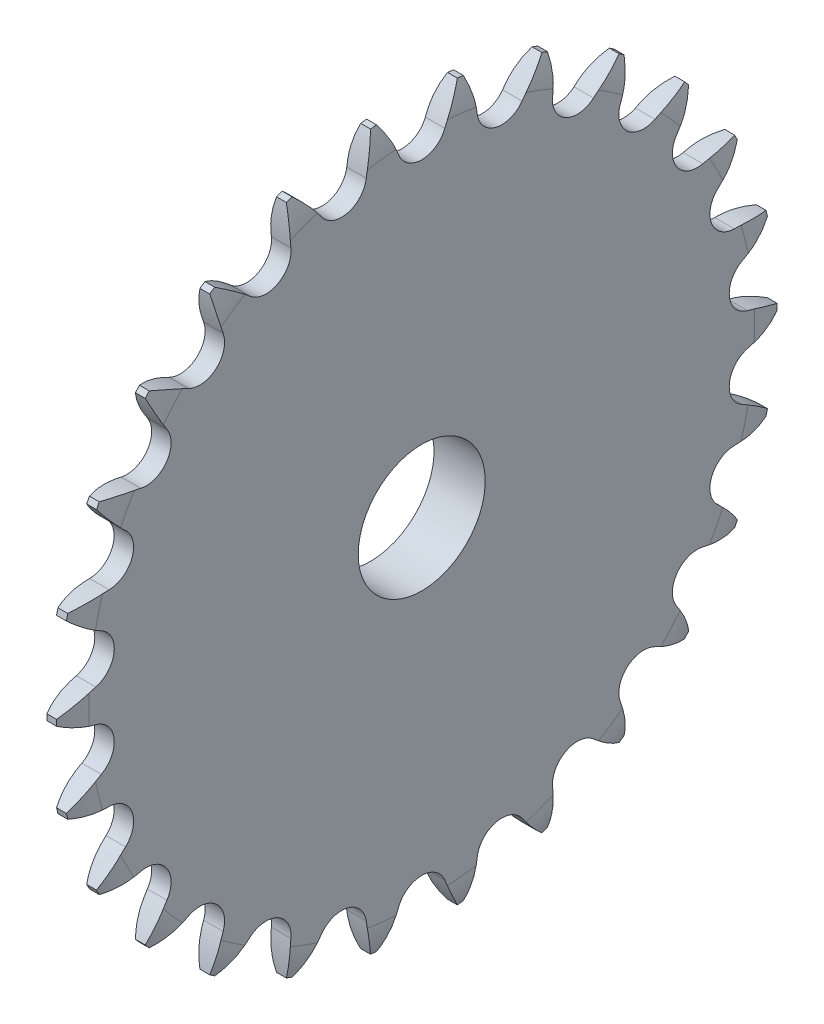
SolidWorks part; units mm, degrees
ref_plane "Plane1" through (0, 0, 0) normal (0, 0, 1) x (1, 0, 0)
ref_plane "Plane2" through (0, 0, 0) normal (0, 1, 0) x (1, 0, 0)
ref_plane "Plane3" through (0, 0, 0) normal (1, 0, 0) x (0, 0, -1)
sketch "Clipboard" plane through (0, 0, 0) normal (0, 1, 0) x (1, 0, 0)
  line L0 (0, 0) -> (11.4147, -5.5673)
  line L1 (-15, 0) -> (100, 0) construction
  line L2 (0, 0) -> (-0.5049, 0.5707)
  line L3 (0, 0) -> (-11.863, 4.5341)
  line L4 (0, 0) -> (2.7863, 1.359)
  line L5 (0, 0) -> (-23.4238, -8.7364)
  line L6 (0, 0) -> (-2.5441, -1.7165)
  line L7 (-0.5049, 0.5707) -> (21.7707, 11.9207)
  line L8 (-76.2, 38.1) -> (-73.4, 38.1)
  line L9 (-73.2427, 39.6204) -> (-72.6435, 39.6525)
  line L10 (-73.1375, 10.4807) -> (-66.1375, 10.4807)
  circle A0 centre (0, 0) radius 3.875
  circle A1 centre (0, 0) radius 21
  circle A2 centre (0, 0) radius 21
  dimension "Dr" = 7.75
  dimension "MHD" = 42
  dimension "Hub_dia" = 42
  dimension "Num_teeth" = 26
  dimension "Pitch" = 12.7
  dimension "Width" = 3.1
  dimension "Side_relief" = 0.762
  dimension "Side_radius" = 12.7
  dimension "Overall_len" = 25
  dimension "Show_teeth" = 26
  dimension "Thickness" = 3.069
  dimension "OAL" = 25.0005
  dimension "T_dim" = 2.8
  dimension "Fillet_rad" = 0.6
  dimension "Face_width" = 3.069
  dimension "Num_strands" = 1
  dimension "Transv_pitch" = 7
  dimension "Plate_wid" = 9.91
sketch "BasProSke" plane through (0, 0, 0) normal (0, 1, 0) x (1, 0, 0)
  line L0 (-10, 0) -> (60, 0) construction
  line L1 (0, 0) -> (0, 52.4106)
  line L2 (0, 0) -> (3.069, 0)
  line L3 (3.069, 0) -> (3.069, 52.4106)
  line L4 (2.307, 56.7436) -> (0.762, 56.7436)
  arc A0 (0, 52.4106) -> (0.762, 56.7436) centre (12.7, 52.4106) cw
  arc A1 (3.069, 52.4106) -> (2.307, 56.7436) centre (-9.631, 52.4106) ccw
  dimension "Thickness" = 3.069
  dimension "D1" = 12.7
  dimension "G1" = 0.762
  dimension "G2" = 0.762
  dimension "Diameter" = 113.4871
revolve "Base-Revolve" add sketch "BasProSke" angle 360 about L0
sketch "TooCutSke" plane through (0, 0, 0) normal (1, 0, 0) x (0, 0, -1)
  line L0 (0, 52.7198) -> (3.6356, 51.2708) construction
  line L1 (0, 0) -> (0, 107) construction
  line L2 (0, 52.7198) -> (-10, 52.7198) construction
  line L3 (0, 52.7198) -> (-3.6356, 51.2708) construction
  arc A0 (3.6356, 51.2708) -> (6.6968, 56.8505) centre (27.8251, 41.6296) cw
  arc A1 (3.6356, 51.2708) -> (-3.6356, 51.2708) centre (0, 52.7198) cw
  arc A2 (-3.6356, 51.2708) -> (-6.6968, 56.8505) centre (-27.8251, 41.6296) ccw
  arc A3 (6.6968, 56.8505) -> (-6.6968, 56.8505) centre (0, 0) ccw
  dimension "R1" = 3.9137
  dimension "R2" = 26.04
  dimension "Overcut" = 57.2436
  dimension "Seat_radius" = 52.7198
  dimension "X" = 136.538
extrude "ToothCut" cut sketch "TooCutSke" along normal through all
pattern_circular "TeethCuts" count 26 every 13.846 about axis through (-10, 0, 0) along (1, 0, 0) of "ToothCut"
sketch "HubNeaOneSke" plane through (0, 0, 0) normal (-1, 0, 0) x (0, 0, 1)
  circle A0 centre (0, 0) radius 21
  dimension "Diameter" = 42
extrude "HubNearOne" add sketch "HubNeaOneSke" along normal blind 5
fillet "HubNearOneFillet" radius 0.6 1 edges at (0, 0, -21)
sketch "HubNeaBotSke" plane through (0, 0, 0) normal (-1, 0, 0) x (0, 0, 1)
  circle A0 centre (0, 0) radius 21
  dimension "Diameter" = 42
extrude "HubNearBoth" [suppressed] add sketch "HubNeaBotSke" along normal blind 10.9657
fillet "HubNearBothFillet" [suppressed] radius 0.6
ref_plane "FarPln" through (3.069, 0, 0) normal (1, 0, 0) x (0, 0, -1)
sketch "HubFarSke" plane through (3.069, 0, 0) normal (1, 0, 0) x (0, 0, -1)
  circle A0 centre (0, 0) radius 21
  dimension "Diameter" = 42
extrude "HubFar" [suppressed] add sketch "HubFarSke" along normal blind 10.9657
fillet "HubFarFillet" [suppressed] radius 0.6
sketch "BorSke" plane through (0, 0, 0) normal (1, 0, 0) x (0, 0, -1)
  circle A0 centre (0, 0) radius 10
  dimension "Diameter" = 20
extrude "Bore" cut sketch "BorSke" along normal mid plane 50.001
sketch "KeySke" plane through (0, 0, 0) normal (1, 0, 0) x (0, 0, -1)
  line L0 (-3, 0) -> (-3, 12.8)
  line L1 (-3, 12.8) -> (3, 12.8)
  line L2 (3, 12.8) -> (3, 0)
  line L3 (0, 0) -> (0, 34) construction
  line L4 (-3, 0) -> (3, 0)
  dimension "Offset" = 12.8
  dimension "Width" = 6
extrude "Keyway" [suppressed] cut sketch "KeySke" along normal mid plane 50.001
pattern_circular "Keyway2" [suppressed] count 2 every 90 about axis through (-10, 0, 0) along (1, 0, 0)
sketch "Эскиз1" plane through (0, 0, 0) normal (0, 0, 1) x (1, 0, 0)
  line L0 (-0.6, 21) -> (-5, 21) construction
  line L1 (4, 21) -> (12, 21)
  line L2 (4, 21) -> (4, 13)
  line L3 (4, 13) -> (12, 13)
  line L4 (12, 21) -> (12, 13)
  line L5 (4, 21) -> (12, 13) construction
  line L6 (4, 13) -> (12, 21) construction
  point P0 (8, 17)
  point P8 (8, 21)
  dimension "D1" = 9
  dimension "D2" = 8
  dimension "D3" = 8
equation "' \"Pitch@Clipboard\" = 12.7"
equation "' \"Num_strands@Clipboard\" = 1"
equation "' \"Num_teeth@Clipboard\" = 9"
equation "' \"Hub_dia@Clipboard\" = 50"
equation "' \"Overall_len@Clipboard\" = 3"
equation "' \"Diameter@BorSke\" = 12"
equation "' \"T_dim@Clipboard\" = 1"
equation "' \"Width@KeySke\" = 2"
equation "' \"Dr@Clipboard\" = 8.51"
equation "' \"Face_width@Clipboard\" = 7.2"
equation "' \"Side_radius@Clipboard\" = 12.7"
equation "' \"Side_relief@Clipboard\" = 1.27"
equation "' \"Transv_pitch@Clipboard\" = 13.92"
equation "' \"Show_teeth@Clipboard\" = 9"
equation "' \"Fillet_rad@Clipboard\" = 0.6"
equation "' \"Plate_wid@Clipboard\" = 11.8"
equation "\"Num_teeth@Clipboard\" = int( \"Num_teeth@Clipboard\" )"
equation "\"Num_teeth@Clipboard\" = ((sgn( \"Num_teeth@Clipboard\" - 5.0)+1)*( \"Num_teeth@Clipboard\" - 5.0))/2 +5.0"
equation "\"Num_teeth@Clipboard\" = ((sgn( \"Num_teeth@Clipboard\" - 200.0)-1)*( \"Num_teeth@Clipboard\" - 200.0))/-2 +200.0"
equation "\"MHD@Clipboard\" = \"Pitch@Clipboard\" * (1.0 / tan(3.14159265 / \"Num_teeth@Clipboard\" )) - 1.04 * \"Plate_wid@Clipboard\" - 0.76"
equation "\"Thickness@Clipboard\"  = \"Face_width@Clipboard\" + (\"Num_strands@Clipboard\" - 1) * \"Transv_pitch@Clipboard\""
equation "\"OAL@Clipboard\" = \"Thickness@Clipboard\" + 2 * \"Fillet_rad@Clipboard\" + 1"
equation "\"MHD@Clipboard\" = ((sgn( \"MHD@Clipboard\" - \"Hub_dia@Clipboard\" )-1)*( \"MHD@Clipboard\" - \"Hub_dia@Clipboard\" ))/-2+ \"Hub_dia@Clipboard\""
equation "\"OAL@Clipboard\" = ((sgn( \"OAL@Clipboard\" - \"Overall_len@Clipboard\" )+1)*( \"OAL@Clipboard\" - \"Overall_len@Clipboard\" ))/2 + \"Overall_len@Clipboard\" + 0.0005"
equation "\"Num_teeth@TeethCuts\" = int( \"Show_teeth@Clipboard\" ) + 1"
equation "\"Num_teeth@TeethCuts\" = ((sgn( \"Num_teeth@TeethCuts\" - \"Num_teeth@Clipboard\" )-1)*( \"Num_teeth@TeethCuts\" - \"Num_teeth@Clipboard\" ))/-2+ \"Num_teeth@Clipboard\""
equation "\"Num_teeth@TeethCuts\" = ((sgn( \"Num_teeth@TeethCuts\" - 2.0)+1)*( \"Num_teeth@TeethCuts\" - 2.0))/2 +2.0"
equation "\"Angle@TeethCuts\" = 360.0 / \"Num_teeth@Clipboard\""
equation "\"Seat_radius@TooCutSke\" = ( \"Pitch@Clipboard\" / 2.0) / sin(3.14159265 / \"Num_teeth@Clipboard\" ) - \"Dr@Clipboard\" / 2.0 + \"Dr@Clipboard\" * 0.505"
equation "\"R1@TooCutSke\"  = \"Dr@Clipboard\" * 0.505"
equation "\"X@TooCutSke\" = 140.0 - (90.0 / \"Num_teeth@Clipboard\")"
equation "\"R2@TooCutSke\" = 0.12 * \"Dr@Clipboard\" * ( \"Num_teeth@Clipboard\" + 2.0)"
equation "\"Overcut@TooCutSke\" = 0.5 + 0.625 * \"Pitch@Clipboard\" - 0.5 * \"Dr@Clipboard\"  +  \"Pitch@Clipboard\" / 2.0 / sin(3.14159265 / \"Num_teeth@Clipboard\" )"
equation "\"Diameter@BasProSke\" = 2.0 * ( 0.625 * \"Pitch@Clipboard\" - 0.5 * \"Dr@Clipboard\"  +  \"Pitch@Clipboard\" / 2.0 / sin(3.14159265 / \"Num_teeth@Clipboard\" ))"
equation "\"Thickness@BasProSke\"  = \"Thickness@Clipboard\""
equation "\"G1@BasProSke\" =  \"Side_relief@Clipboard\""
equation "\"G2@BasProSke\" =  \"Side_relief@Clipboard\""
equation "\"D1@BasProSke\" =  \"Side_radius@Clipboard\""
equation "\"Diameter@HubNeaOneSke\" = \"MHD@Clipboard\""
equation "\"Diameter@HubNeaBotSke\" = \"MHD@Clipboard\""
equation "\"Length@HubNearBoth\" = ( \"OAL@Clipboard\" - \"Thickness@BasProSke\" ) / 2.0"
equation "\"D1@HubNearOneFillet\" = \"Fillet_rad@Clipboard\""
equation "\"D1@HubNearBothFillet\" = \"Fillet_rad@Clipboard\""
equation "\"Thickness@FarPln\" = \"Thickness@BasProSke\""
equation "\"Diameter@HubFarSke\" = \"MHD@Clipboard\""
equation "\"Length@HubFar\" = ( \"OAL@Clipboard\" - \"Thickness@BasProSke\" ) / 2.0"
equation "\"D1@HubFarFillet\" = \"Fillet_rad@Clipboard\""
equation "\"D1@Bore\" = \"OAL@Clipboard\" * 2.0"
equation "\"D1@Keyway\" = \"OAL@Clipboard\" * 2.0"
equation "\"Offset@KeySke\" = \"T_dim@Clipboard\" + \"Diameter@BorSke\" / 2.0"
